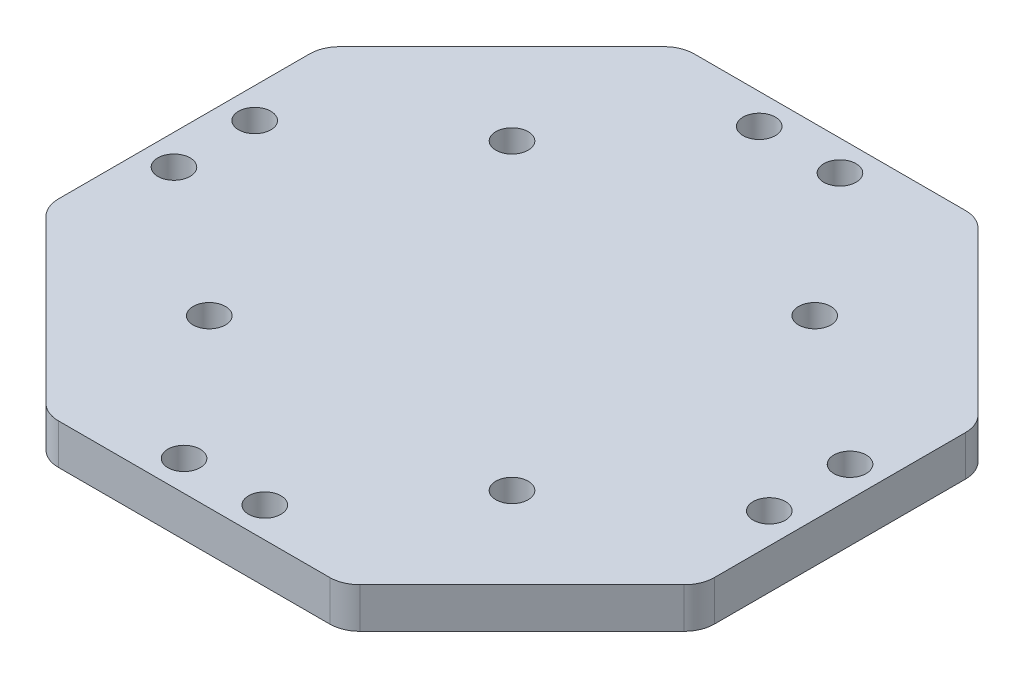
SolidWorks part; units mm, degrees
ref_plane "前视基准面" through (0, 0, 0) normal (0, 0, 1) x (1, 0, 0)
ref_plane "上视基准面" through (0, 0, 0) normal (0, 1, 0) x (1, 0, 0)
ref_plane "右视基准面" through (0, 0, 0) normal (1, 0, 0) x (0, 0, -1)
sketch "草图1" plane through (0, 0, 0) normal (0, 1, 0) x (1, 0, 0)
  line L1 (-32.5, 31.5) -> (32.5, 31.5)
  line L2 (-32.5, 31.5) -> (-32.5, -31.5)
  line L3 (-32.5, -31.5) -> (32.5, -31.5)
  line L4 (32.5, 31.5) -> (32.5, -31.5)
  line L5 (-32.5, 31.5) -> (32.5, -31.5) construction
  line L6 (-32.5, -31.5) -> (32.5, 31.5) construction
  point P0 (0, 0)
  dimension "D1" = 65
  dimension "D2" = 63
extrude "凸台-拉伸1" add sketch "草图1" along normal blind 4
sketch "草图2" plane through (0, 4, 0) normal (0, 1, 0) x (1, 0, 0)
  line L0 (-32.5, 0) -> (32.5, 0) construction
  line L1 (-32.5, 31.5) -> (-32.5, -31.5) construction
  line L2 (32.5, -31.5) -> (32.5, 31.5) construction
  line L3 (0, -31.5) -> (0, 31.5) construction
  line L4 (-32.5, -31.5) -> (32.5, -31.5) construction
  line L5 (32.5, 31.5) -> (-32.5, 31.5) construction
  line L11 (-20, 20) -> (20, -20) construction
  line L12 (-20, -20) -> (20, 20) construction
  circle A0 centre (-15, -15) radius 1.6
  circle A1 centre (-15, 15) radius 1.6
  circle A2 centre (15, 15) radius 1.6
  circle A3 centre (15, -15) radius 1.6
  point P12 (0, 0)
  dimension "D3" = 15
  dimension "D4" = 3.2
  dimension "D5" = 30
  dimension "D1" = 40
  dimension "D2" = 40
extrude "切除-拉伸1" cut sketch "草图2" against normal blind 4
sketch "草图3" plane through (0, 4, 0) normal (0, 1, 0) x (1, 0, 0)
  line L0 (0, 31.5) -> (0, -31.5) construction
  line L1 (32.5, 31.5) -> (-32.5, 31.5) construction
  line L2 (-32.5, -31.5) -> (32.5, -31.5) construction
  line L3 (32.5, 0) -> (-32.5, 0) construction
  line L4 (-32.5, 31.5) -> (-32.5, -31.5) construction
  line L5 (32.5, -31.5) -> (32.5, 31.5) construction
  line L6 (-32.5, 31.5) -> (-32.5, -31.5) construction
  circle A1 centre (-4, -28.5) radius 1.6
  circle A2 centre (-15, -15) radius 1.6 construction
  circle A3 centre (4, -28.5) radius 1.6
  circle A4 centre (4, 28.5) radius 1.6
  circle A5 centre (-4, 28.5) radius 1.6
  circle A6 centre (-29.5, -4) radius 1.6
  circle A7 centre (-29.5, 4) radius 1.6
  circle A8 centre (29.5, 4) radius 1.6
  circle A9 centre (29.5, -4) radius 1.6
  dimension "D1" = 13.5
  dimension "D2" = 3.2
  dimension "D3" = 4
  dimension "D4" = 3
  dimension "D5" = 4
  dimension "D6" = 3.2
extrude "切除-拉伸2" cut sketch "草图3" against normal blind 4
fillet "圆角1" radius 3 4 edges at (32.5, 2, 31.5) (-32.5, 2, -31.5) (32.5, 2, -31.5) (-32.5, 2, 31.5)
sketch "草图5" plane through (0, 4, 0) normal (0, 1, 0) x (1, 0, 0)
  line L0 (-29.5, -31.5) -> (29.5, -31.5) construction
  line L1 (-47.6822, -46.6822) -> (-9.6818, -36.5)
  line L2 (-9.6818, -36.5) -> (-37.5, -8.6818)
  line L3 (-37.5, -8.6818) -> (-47.6822, -46.6822)
  line L4 (-32.5, 28.5) -> (-32.5, -28.5) construction
  line L5 (0, 31.5) -> (0, -31.5) construction
  line L6 (29.5, 31.5) -> (-29.5, 31.5) construction
  line L7 (-32.5, 0) -> (32.5, 0) construction
  line L8 (32.5, -28.5) -> (32.5, 28.5) construction
  line L9 (37.5, -8.6818) -> (47.6822, -46.6822)
  line L10 (47.6822, -46.6822) -> (9.6818, -36.5)
  line L11 (9.6818, -36.5) -> (37.5, -8.6818)
  line L12 (-37.5, 8.6818) -> (-47.6822, 46.6822)
  line L13 (-9.6818, 36.5) -> (-37.5, 8.6818)
  line L14 (-47.6822, 46.6822) -> (-9.6818, 36.5)
  line L15 (37.5, 8.6818) -> (47.6822, 46.6822)
  line L16 (9.6818, 36.5) -> (37.5, 8.6818)
  line L17 (47.6822, 46.6822) -> (9.6818, 36.5)
  circle A0 centre (-31.6213, -30.6213) radius 11.3567 construction
  arc A1 (-32.5, -28.5) -> (-29.5, -31.5) centre (-29.5, -28.5) ccw construction
  circle A3 centre (-31.6213, 30.6213) radius 11.3567 construction
  dimension "D1" = 5
  dimension "D2" = 5
extrude "切除-拉伸3" cut sketch "草图5" against normal blind 10
fillet "圆角2" radius 3 8 edges at (32.5, 2, -13.6818) (14.6818, 2, -31.5) (-14.6818, 2, -31.5) (-32.5, 2, -13.6818) (-14.6818, 2, 31.5) (14.6818, 2, 31.5) (32.5, 2, 13.6818) (-32.5, 2, 13.6818)
